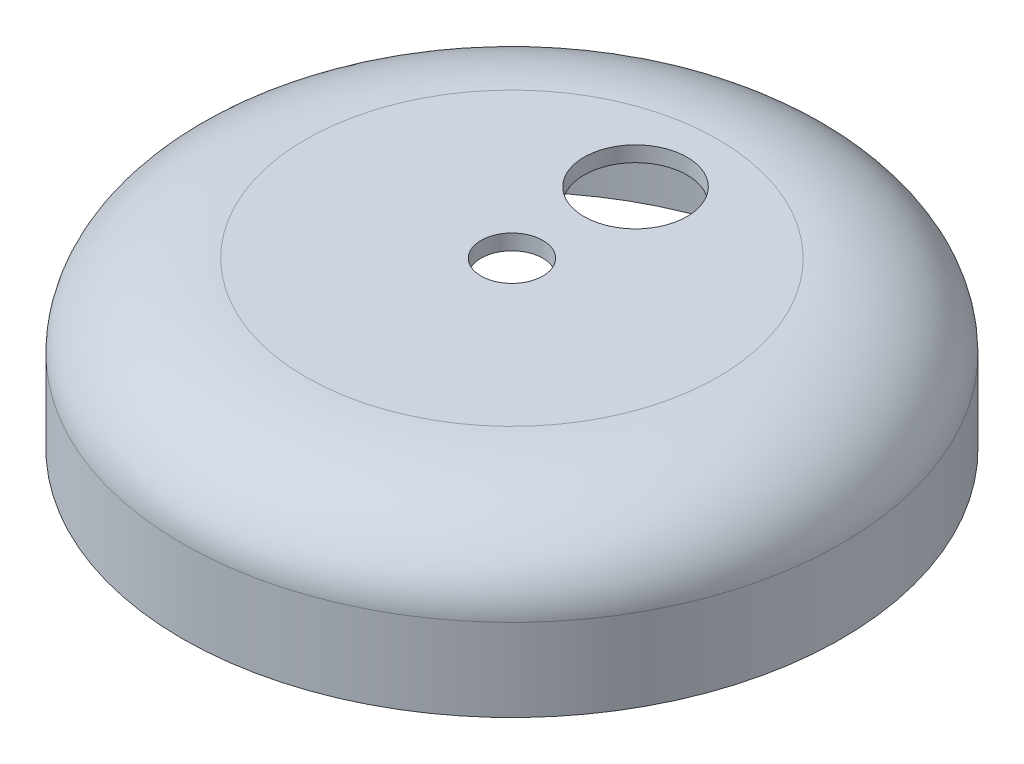
SolidWorks part; units mm, degrees
material "6061-T6 (SS)"
ref_plane "Front" through (0, 0, 0) normal (0, 0, 1) x (1, 0, 0)
ref_plane "Top" through (0, 0, 0) normal (0, 1, 0) x (1, 0, 0)
ref_plane "Right" through (0, 0, 0) normal (1, 0, 0) x (0, 0, -1)
sketch "Sketch1" plane through (0, 0, 0) normal (0, 0, 1) x (1, 0, 0)
  line L0 (0, 0) -> (101.6, 0) construction
  line L1 (101.6, 0) -> (101.6, -67.9188) construction
  line L2 (0, 29.5111) -> (0, -26.7187) construction
  line L3 (0, 0) -> (0, -4.7625)
  line L4 (0, 0) -> (63.5, 0)
  line L5 (0, -4.7625) -> (63.5, -4.7625)
  line L6 (101.6, 5.9654) -> (96.8375, 5.9654) construction
  line L7 (96.8375, 5.9654) -> (96.8375, -58.8285) construction
  line L9 (63.5, -25.4) -> (127.5739, -25.4) construction
  line L12 (63.5, 0) -> (63.5, -38.8167) construction
  line L14 (96.8375, -50.8) -> (101.6, -50.8)
  line L15 (101.6, -50.8) -> (101.6, -25.4)
  line L16 (96.8375, -50.8) -> (96.8375, -25.4)
  ellipse E0 centre (63.5, -25.4) end of major axis (96.8375, -25.4) minor radius 20.6375 (96.8375, -25.4) -> (63.5, -4.7625) ccw
  ellipse E1 centre (63.5, -25.4) end of major axis (25.4, -25.4) minor radius 25.4 (63.5, 0) -> (101.6, -25.4) cw
  dimension "D1" = 101.6
  dimension "D2" = 63.5
  dimension "D3" = 25.4
  dimension "D4" = 4.7625
  dimension "D5" = 4.7625
  dimension "D6" = 25.4
revolve "Revolve1" add sketch "Sketch1" angle 360 about L2
sketch "Sketch2" plane through (0, 0, 0) normal (0, 1, 0) x (1, 0, 0)
  line L0 (0, 0) -> (0, 199.7485) construction
  line L1 (0, 0) -> (303.3008, 0) construction
  circle A0 centre (0, 38.1) radius 15.875
  circle A1 centre (0, 0) radius 9.525
  dimension "D1" = 31.75
  dimension "D3" = 19.05
  dimension "D2" = 38.1
extrude "Cut-Extrude1" cut sketch "Sketch2" against normal blind 25.4
